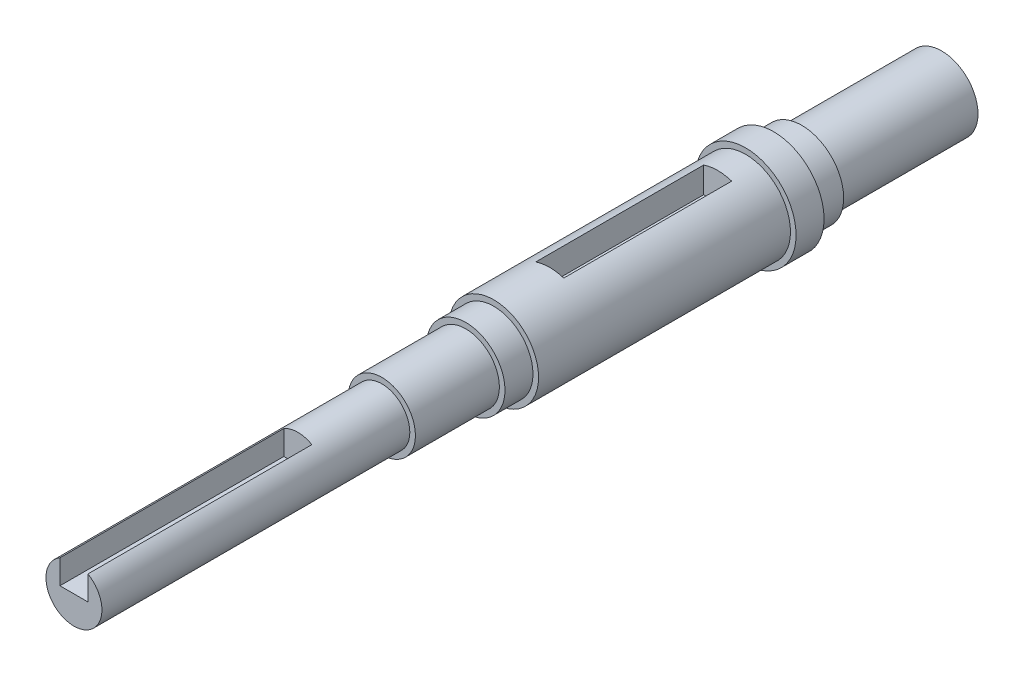
SolidWorks part; units mm, degrees
ref_plane "Front Plane" through (0, 0, 0) normal (0, 0, 1) x (1, 0, 0)
ref_plane "Top Plane" through (0, 0, 0) normal (0, 1, 0) x (1, 0, 0)
ref_plane "Right Plane" through (0, 0, 0) normal (1, 0, 0) x (0, 0, -1)
sketch "Sketch1" plane through (0, 0, 0) normal (1, 0, 0) x (0, 0, -1)
  line L0 (0, 0) -> (0, 6.35)
  line L1 (69.85, 6.35) -> (69.85, 7.62)
  line L2 (69.85, 7.62) -> (88.9, 7.62)
  line L3 (88.9, 7.62) -> (88.9, 8.89)
  line L5 (0, 0) -> (196.85, 0)
  line L6 (152.4, 10.16) -> (152.4, 11.43)
  line L7 (152.4, 11.43) -> (158.75, 11.43)
  line L8 (158.75, 11.43) -> (158.75, 9.525)
  line L9 (158.75, 9.525) -> (165.1, 9.525)
  line L10 (165.1, 9.525) -> (165.1, 8.255)
  line L11 (165.1, 8.255) -> (196.85, 8.255)
  line L12 (196.85, 8.255) -> (196.85, 0)
  line L13 (165.1, 8.255) -> (152.4, 8.255) construction
  line L14 (88.9, 7.62) -> (101.6, 7.62) construction
  line L15 (69.85, 6.35) -> (0, 6.35)
  line L16 (152.4, 10.16) -> (95.25, 10.16)
  line L17 (88.9, 8.89) -> (95.25, 8.89)
  line L18 (95.25, 8.89) -> (95.25, 10.16)
  point P14 (0, 0)
  dimension "D2" = 31.75
  dimension "D4" = 69.85
  dimension "D1" = 12.7
  dimension "D3" = 50.8
  dimension "D5" = 19.05
  dimension "D6" = 6.35
  dimension "D7" = 8.255
  dimension "D8" = 9.525
  dimension "D9" = 11.43
  dimension "D10" = 10.16
  dimension "D11" = 8.89
  dimension "D12" = 7.62
  dimension "D13" = 6.35
revolve "Revolve1" add sketch "Sketch1" angle 360 about L5
ref_plane "Plane1" through (0, 6.35, 0) normal (0, 1, 0) x (1, 0, 0)
ref_plane "Plane2" through (0, 10.16, 0) normal (0, 1, 0) x (1, 0, 0)
sketch "Sketch2" plane through (0, 6.35, 0) normal (0, 1, 0) x (1, 0, 0)
  line L0 (-6.35, 0) -> (6.35, 0) construction
  line L1 (-3.175, 0) -> (3.175, 0)
  line L2 (-3.175, 0) -> (-3.175, 50.8)
  line L3 (-3.175, 50.8) -> (3.175, 50.8)
  line L4 (3.175, 0) -> (3.175, 50.8)
  point P6 (0, 0)
  dimension "D1" = 6.35
  dimension "D2" = 50.8
extrude "Cut-Extrude1" cut sketch "Sketch2" against normal blind 6.35
sketch "Sketch3" plane through (0, 10.16, 0) normal (0, 1, 0) x (1, 0, 0)
  line L1 (-3.175, 107.95) -> (3.175, 107.95)
  line L2 (-3.175, 107.95) -> (-3.175, 146.05)
  line L3 (-3.175, 146.05) -> (3.175, 146.05)
  line L4 (3.175, 107.95) -> (3.175, 146.05)
  point P4 (0, 107.95)
  point P7 (0, 146.05)
  dimension "D1" = 6.35
  dimension "D2" = 6.35
  dimension "D3" = 6.35
extrude "Cut-Extrude3" cut sketch "Sketch3" against normal blind 6.35
equation "\"FaceWidth\"= 2"
equation "\"D3@Sketch1\"=\"FaceWidth\""
equation "\"Do1\"= .65"
equation "\"Do2\" = .75"
equation "\"Do3\" = .9"
equation "\"Do4\" = .8"
equation "\"Do5\" = .7"
equation "\"Do6\" = .6"
equation "\"Do7\" = .5"
equation "\"D7@Sketch1\"=\"Do1\"/2"
equation "\"D8@Sketch1\"=\"Do2\"/2"
equation "\"D9@Sketch1\"=\"Do3\"/2"
equation "\"D10@Sketch1\"=\"Do4\"/2"
equation "\"D11@Sketch1\"=\"Do5\"/2"
equation "\"D12@Sketch1\"=\"Do6\"/2"
equation "\"D13@Sketch1\"=\"Do7\"/2"
